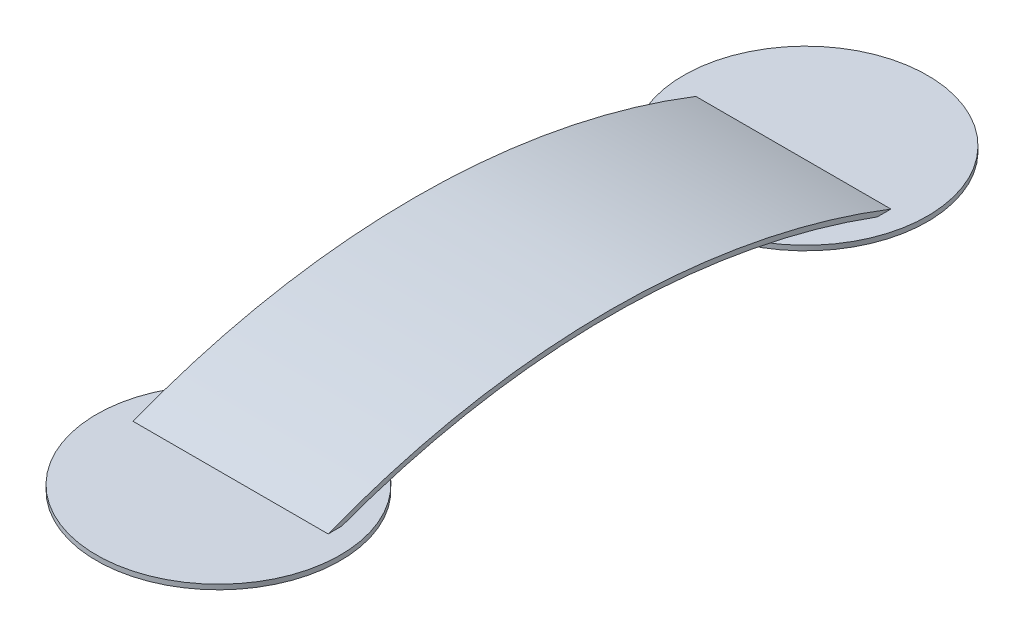
SolidWorks part; units mm, degrees
ref_plane "Front Plane" through (0, 0, 0) normal (0, 0, 1) x (1, 0, 0)
ref_plane "Top Plane" through (0, 0, 0) normal (0, 1, 0) x (1, 0, 0)
ref_plane "Right Plane" through (0, 0, 0) normal (1, 0, 0) x (0, 0, -1)
sketch "Sketch1" plane through (0, 0, 0) normal (1, 0, 0) x (0, 0, -1)
  line L0 (-11.5, 0) -> (-12.037, 0)
  line L1 (0, 6.8084) -> (0, -5.9787) construction
  line L2 (11.5, 0) -> (12.037, 0)
  arc A0 (-12.037, 0) -> (12.037, 0) centre (0, -29.327) cw
  arc A1 (-11.5, 0) -> (11.5, 0) centre (0, -29.327) cw
  arc A2 (-11.9611, -0.185) -> (11.9611, -0.185) centre (0, -29.327) cw construction
  dimension "D2" = 23
  dimension "D1" = 0.2
extrude "Boss-Extrude1" add sketch "Sketch1" along normal blind 8
sketch "Sketch2" plane through (0, 0, 0) normal (0, 1, 0) x (1, 0, 0)
  line L0 (8, 12.037) -> (0, 12.037) construction
  line L1 (0, 0) -> (-7.2977, 0) construction
  circle A0 centre (4, 12.037) radius 5
  circle A1 centre (4, -12.037) radius 5
  dimension "D1" = 10
extrude "Boss-Extrude2" add sketch "Sketch2" along normal blind 0.2
